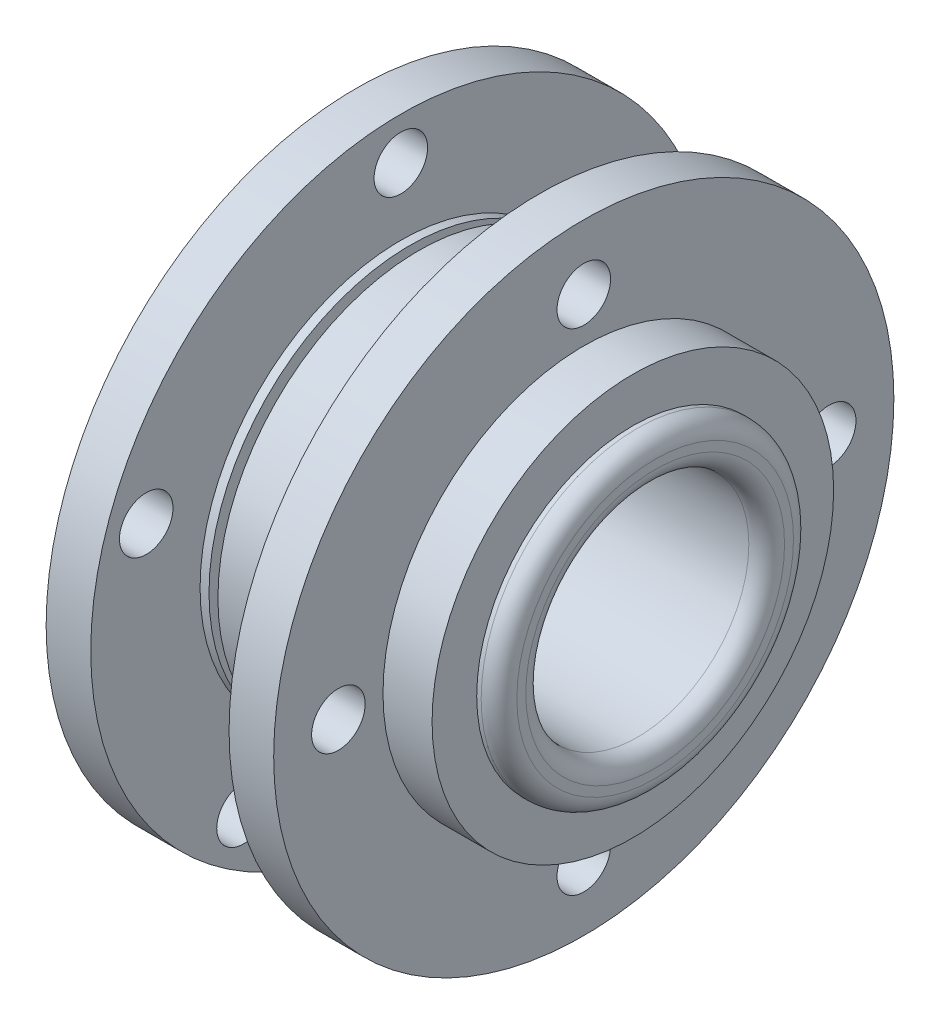
SolidWorks part; units mm, degrees
ref_plane "Płaszczyzna przednia" through (0, 0, 0) normal (0, 0, 1) x (1, 0, 0)
ref_plane "Płaszczyzna górna" through (0, 0, 0) normal (0, 1, 0) x (1, 0, 0)
ref_plane "Płaszczyzna prawa" through (0, 0, 0) normal (1, 0, 0) x (0, 0, -1)
sketch "Szkic2" plane through (0, 0, 0) normal (0, 0, 1) x (1, 0, 0)
  line L0 (82, 0) -> (82, 45)
  line L1 (55, 0) -> (-55, 0) construction
  line L2 (82, 45) -> (66, 45)
  line L3 (66, 45) -> (66, 69.5)
  line L4 (66, 69.5) -> (56, 69.5)
  line L5 (56, 69.5) -> (56, 45)
  line L6 (56, 45) -> (25, 45)
  line L7 (25, 45) -> (25, 69.5)
  line L8 (25, 69.5) -> (15, 69.5)
  line L9 (15, 69.5) -> (15, 39.5)
  line L10 (15, 39.5) -> (0, 39.5)
  line L11 (0, 39.5) -> (0, 0)
  line L12 (0, 0) -> (82, 0)
  line L13 (0, -55) -> (0, 55) construction
  point P14 (66, 57.25)
  point P15 (23.9533, 69.5)
  dimension "D1" = 45
  dimension "D2" = 39.5
  dimension "D3" = 69.5
  dimension "D4" = 69.5
  dimension "D5" = 51
  dimension "D6" = 10
  dimension "D7" = 45
  dimension "D8" = 82
  dimension "D9" = 15
  dimension "D10" = 16
  dimension "D11" = 0
revolve "Obrót1" add sketch "Szkic2" angle 360 about L12
sketch "Szkic4" plane through (66, 0, 0) normal (1, 0, 0) x (0, 0, -1)
  line L0 (0, 45.1) -> (0, -45.1) construction
  line L1 (45.1, 0) -> (-45.1, 0) construction
  circle A0 centre (0, 55) radius 6
  circle A1 centre (55, 0) radius 6
  circle A2 centre (0, -55) radius 6
  circle A3 centre (-55, 0) radius 6
  point P15 (0, 0)
  dimension "D1" = 12
  dimension "D2" = 55
  dimension "D3" = 4
extrude "Wytnij-wyciągnięcie1" cut sketch "Szkic4" against normal blind 10
sketch "Szkic5" plane through (15, 0, 0) normal (-1, 0, 0) x (0, 0, 1)
  line L0 (0, -45.1) -> (0, 45.1) construction
  line L1 (45.1, 0) -> (-45.1, 0) construction
  circle A0 centre (0, 60) radius 6
  circle A1 centre (57.0634, 18.541) radius 6
  circle A2 centre (35.2671, -48.541) radius 6
  circle A3 centre (-35.2671, -48.541) radius 6
  circle A4 centre (-57.0634, 18.541) radius 6
  point P17 (0, 0)
  dimension "D1" = 12
  dimension "D2" = 60
  dimension "D3" = 5
extrude "Wytnij-wyciągnięcie2" cut sketch "Szkic5" against normal blind 10
sketch "Szkic6" plane through (0, 0, 0) normal (-1, 0, 0) x (0, 0, 1)
  circle A0 centre (0, 0) radius 35
  dimension "D1" = 70
extrude "Wytnij-wyciągnięcie3" cut sketch "Szkic6" against normal blind 15
sketch "Szkic7" plane through (82, 0, 0) normal (1, 0, 0) x (0, 0, -1)
  circle A0 centre (0, 0) radius 35
  circle A1 centre (0, 0) radius 45
  dimension "D1" = 90
  dimension "D2" = 70
extrude "Wytnij-wyciągnięcie4" cut sketch "Szkic7" against normal blind 5
sketch "Szkic8" plane through (82, 0, 0) normal (1, 0, 0) x (0, 0, -1)
  circle A0 centre (0, 0) radius 25
  dimension "D1" = 50
extrude "Wytnij-wyciągnięcie5" cut sketch "Szkic8" against normal blind 70
fillet "Zaokrąglenie1" radius 4 2 edges at (82, 0, -35) (82, 0, -25)
sketch "Szkic9" plane through (0, 0, 0) normal (0, 0, 1) x (1, 0, 0)
  line L0 (56, 45) -> (25, 45) construction
  line L1 (27, 45) -> (29, 45)
  line L2 (27, 45) -> (27, 42)
  line L3 (27, 42) -> (29, 42)
  line L4 (29, 45) -> (29, 42)
  line L6 (25, -69.5) -> (25, 69.5) construction
  dimension "D1" = 2
  dimension "D2" = 3
  dimension "D3" = 2
ref_axis "Oś2" through (-4.1, 0, 0) along (1, 0, 0)
revolve "Wycięcie-obrót1" cut sketch "Szkic9" angle 360 about axis through (-4.1, 0, 0) along (1, 0, 0)
